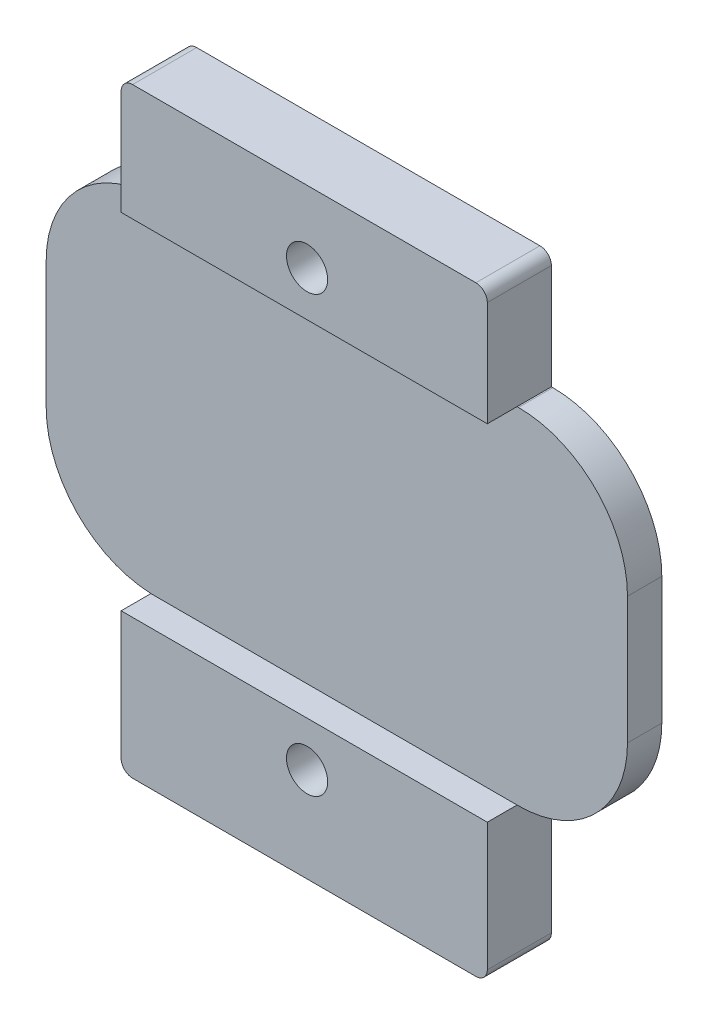
SolidWorks part; units mm, degrees
ref_plane "Front Plane" through (0, 0, 0) normal (0, 0, 1) x (1, 0, 0)
ref_plane "Top Plane" through (0, 0, 0) normal (0, 1, 0) x (1, 0, 0)
ref_plane "Right Plane" through (0, 0, 0) normal (1, 0, 0) x (0, 0, -1)
sketch "Sketch1" plane through (0, 0, 0) normal (0, 0, 1) x (1, 0, 0)
  line L0 (-13.25, 13.25) -> (14.75, 13.25) construction
  line L5 (14.75, -39.25) -> (-15.25, -39.25) construction
  line L6 (15.75, 12.25) -> (15.75, -38.25) construction
  line L7 (-15.25, 13.25) -> (14.75, 13.25)
  line L8 (14.75, -39.25) -> (-15.25, -39.25)
  line L9 (15.75, 12.25) -> (15.75, -38.25)
  line L10 (-16.25, 12.25) -> (-16.25, -38.25)
  arc A0 (15.75, 12.25) -> (14.75, 13.25) centre (14.75, 12.25) ccw construction
  arc A1 (-16.25, 12.25) -> (-15.25, 13.25) centre (-15.25, 12.25) cw
  arc A2 (-16.25, -38.25) -> (-15.25, -39.25) centre (-15.25, -38.25) ccw construction
  arc A3 (14.75, -39.25) -> (15.75, -38.25) centre (14.75, -38.25) ccw construction
  arc A4 (15.75, 12.25) -> (14.75, 13.25) centre (14.75, 12.25) ccw
  arc A6 (-16.25, -38.25) -> (-15.25, -39.25) centre (-15.25, -38.25) ccw
  arc A7 (14.75, -39.25) -> (15.75, -38.25) centre (14.75, -38.25) ccw
  dimension "D1" = 1
extrude "Boss-Extrude1" add sketch "Sketch1" along normal blind 3
sketch "Sketch2" plane through (0, 0, 3) normal (0, 0, 1) x (1, 0, 0)
  line L0 (-36, -12) -> (0.0052, -12) construction
  line L2 (15.75, -38.25) -> (15.75, 12.25) construction
  line L3 (-15.25, -39.25) -> (14.75, -39.25) construction
  line L4 (15.75, -38.25) -> (15.75, -27.075)
  line L5 (-15.25, -39.25) -> (14.75, -39.25)
  line L6 (14.75, 13.25) -> (-15.25, 13.25) construction
  line L7 (-16.25, -27.075) -> (15.75, -27.075)
  line L8 (-16.25, -27.075) -> (-16.25, -38.25)
  line L9 (-16.25, 12.25) -> (-16.25, -38.25) construction
  line L10 (15.75, -38.25) -> (15.75, -27.075) construction
  line L16 (14.75, 13.25) -> (-15.25, 13.25)
  line L17 (-16.25, 12.25) -> (-16.25, 3.075)
  line L18 (-16.25, 3.075) -> (15.75, 3.075)
  line L19 (-16.25, -27.075) -> (-16.25, -38.25) construction
  line L20 (15.75, 3.075) -> (15.75, 12.25)
  arc A0 (14.75, -39.25) -> (15.75, -38.25) centre (14.75, -38.25) ccw construction
  arc A1 (-16.25, -38.25) -> (-15.25, -39.25) centre (-15.25, -38.25) ccw construction
  arc A2 (14.75, -39.25) -> (15.75, -38.25) centre (14.75, -38.25) ccw
  arc A3 (-16.25, -38.25) -> (-15.25, -39.25) centre (-15.25, -38.25) ccw
  arc A4 (15.75, 12.25) -> (14.75, 13.25) centre (14.75, 12.25) ccw construction
  circle A6 centre (-36, -12) radius 6 construction
  arc A9 (15.75, 12.25) -> (14.75, 13.25) centre (14.75, 12.25) ccw
  circle A15 centre (-36, -12) radius 6 construction
  arc A16 (-15.25, 13.25) -> (-16.25, 12.25) centre (-15.25, 12.25) ccw
  dimension "D3" = 1
  dimension "D1" = 15.075
  dimension "D2" = 15.075
extrude "Boss-Extrude2" add sketch "Sketch2" along normal blind 2.6
sketch "Sketch6" plane through (0, 0, 5.6) normal (0, 0, 1) x (1, 0, 0)
  line L0 (15.875, 3.0748) -> (14.732, 3.0748) construction
  line L1 (14.732, 3.0748) -> (14.732, -27.075) construction
  line L2 (14.732, -27.075) -> (15.875, -27.075) construction
  line L3 (25.4, -17.55) -> (25.4, -6.4502) construction
  line L4 (-14.732, -27.075) -> (-14.732, 3.0748) construction
  line L5 (-14.732, 3.0748) -> (-15.875, 3.0748) construction
  line L6 (-25.4, -6.4502) -> (-25.4, -17.55) construction
  line L7 (-15.875, -27.075) -> (-14.732, -27.075) construction
  line L8 (15.875, 3.0748) -> (14.732, 3.0748)
  line L9 (14.732, 3.0748) -> (14.732, -27.075)
  line L10 (14.732, -27.075) -> (15.875, -27.075)
  line L11 (25.4, -17.55) -> (25.4, -6.4502)
  line L12 (-14.732, -27.075) -> (-14.732, 3.0748)
  line L13 (-14.732, 3.0748) -> (-15.875, 3.0748)
  line L14 (-25.4, -6.4502) -> (-25.4, -17.55)
  line L15 (-15.875, -27.075) -> (-14.732, -27.075)
  arc A0 (15.875, -27.075) -> (25.4, -17.55) centre (15.875, -17.55) ccw construction
  arc A1 (25.4, -6.4502) -> (15.875, 3.0748) centre (15.875, -6.4502) ccw construction
  arc A2 (-15.875, 3.0748) -> (-25.4, -6.4502) centre (-15.875, -6.4502) ccw construction
  arc A3 (-25.4, -17.55) -> (-15.875, -27.075) centre (-15.875, -17.55) ccw construction
  arc A4 (15.875, -27.075) -> (25.4, -17.55) centre (15.875, -17.55) ccw
  arc A5 (25.4, -6.4502) -> (15.875, 3.0748) centre (15.875, -6.4502) ccw
  arc A6 (-15.875, 3.0748) -> (-25.4, -6.4502) centre (-15.875, -6.4502) ccw
  arc A7 (-25.4, -17.55) -> (-15.875, -27.075) centre (-15.875, -17.55) ccw
sketch "Sketch7" plane through (0, 0, 3) normal (0, 0, 1) x (1, 0, 0)
  line L0 (-14.732, 3.0748) -> (14.732, 3.0748)
  line L1 (-14.732, -27.075) -> (14.732, -27.075)
  line L4 (15.875, 3.0748) -> (14.732, 3.0748)
  line L5 (14.732, 3.0748) -> (14.732, -27.075)
  line L6 (14.732, -27.075) -> (15.875, -27.075)
  line L7 (25.4, -17.55) -> (25.4, -6.4502)
  line L8 (15.875, 3.0748) -> (14.732, 3.0748)
  line L9 (14.732, 3.0748) -> (14.732, -27.075) construction
  line L10 (14.732, -27.075) -> (15.875, -27.075)
  line L11 (25.4, -17.55) -> (25.4, -6.4502)
  line L12 (-14.732, 3.0748) -> (-15.875, 3.0748)
  line L13 (-14.732, -27.075) -> (-14.732, 3.0748)
  line L14 (-15.875, -27.075) -> (-14.732, -27.075)
  line L15 (-25.4, -6.4502) -> (-25.4, -17.55)
  line L16 (-14.732, 3.0748) -> (-15.875, 3.0748)
  line L17 (-14.732, -27.075) -> (-14.732, 3.0748) construction
  line L18 (-15.875, -27.075) -> (-14.732, -27.075)
  line L19 (-25.4, -6.4502) -> (-25.4, -17.55)
  arc A2 (15.875, -27.075) -> (25.4, -17.55) centre (15.875, -17.55) ccw
  arc A3 (25.4, -6.4502) -> (15.875, 3.0748) centre (15.875, -6.4502) ccw
  arc A4 (15.875, -27.075) -> (25.4, -17.55) centre (15.875, -17.55) ccw
  arc A5 (25.4, -6.4502) -> (15.875, 3.0748) centre (15.875, -6.4502) ccw
  arc A6 (-25.4, -17.55) -> (-15.875, -27.075) centre (-15.875, -17.55) ccw
  arc A7 (-15.875, 3.0748) -> (-25.4, -6.4502) centre (-15.875, -6.4502) ccw
  arc A8 (-25.4, -17.55) -> (-15.875, -27.075) centre (-15.875, -17.55) ccw
  arc A9 (-15.875, 3.0748) -> (-25.4, -6.4502) centre (-15.875, -6.4502) ccw
  dimension "D1" = 0
  dimension "D2" = 0
extrude "Boss-Extrude3" add sketch "Sketch7" against normal up to surface (3 mm away) up to face at (-0.25, -13, 0)
sketch "Sketch8" plane through (0, 0, 0) normal (0, 0, 1) x (1, 0, 0)
  circle A2 centre (0, 7) radius 1.8
  circle A3 centre (0, -31) radius 1.8
extrude "Cut-Extrude2" cut sketch "Sketch8" along normal blind 8
